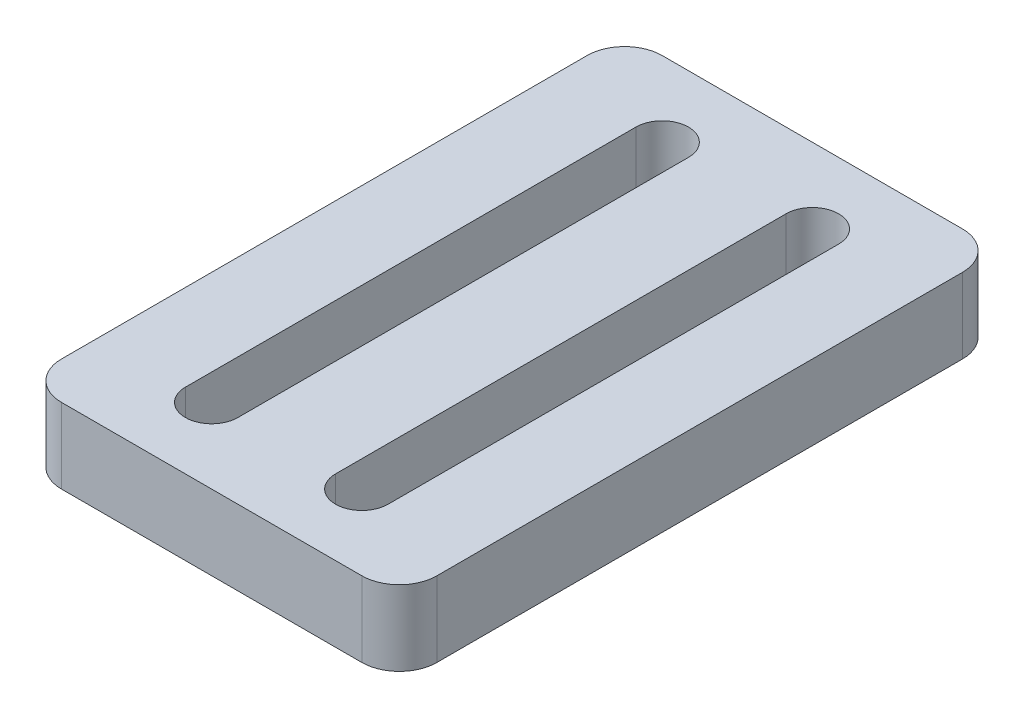
SolidWorks part; units mm, degrees
ref_plane "Front Plane" through (0, 0, 0) normal (0, 0, 1) x (1, 0, 0)
ref_plane "Top Plane" through (0, 0, 0) normal (0, 1, 0) x (1, 0, 0)
ref_plane "Right Plane" through (0, 0, 0) normal (1, 0, 0) x (0, 0, -1)
sketch "Sketch1" plane through (0, 0, 0) normal (0, 1, 0) x (1, 0, 0)
  line L1 (-12.5, -20) -> (12.5, -20)
  line L2 (-12.5, -20) -> (-12.5, 20)
  line L3 (-12.5, 20) -> (12.5, 20)
  line L4 (12.5, -20) -> (12.5, 20)
  line L5 (-12.5, -20) -> (12.5, 20) construction
  line L6 (-12.5, 20) -> (12.5, -20) construction
  point P0 (0, 0)
  dimension "D1" = 25
  dimension "D2" = 40
extrude "Boss-Extrude1" add sketch "Sketch1" along normal blind 5
sketch "Sketch2" plane through (0, 5, 0) normal (0, 1, 0) x (1, 0, 0)
  line L0 (-5, 15) -> (-5, -15) construction
  line L1 (-3.25, 15) -> (-3.25, -15)
  line L2 (-6.75, 15) -> (-6.75, -15)
  line L3 (12.5, 20) -> (-12.5, 20) construction
  line L4 (-12.5, 20) -> (-12.5, -20) construction
  line L5 (-12.5, -20) -> (12.5, -20) construction
  line L6 (0, 0) -> (0, 19.657) construction
  line L7 (5, 15) -> (5, -15) construction
  line L8 (3.25, 15) -> (3.25, -15)
  line L9 (6.75, 15) -> (6.75, -15)
  arc A0 (-3.25, 15) -> (-6.75, 15) centre (-5, 15) ccw
  arc A1 (-6.75, -15) -> (-3.25, -15) centre (-5, -15) ccw
  arc A2 (3.25, 15) -> (6.75, 15) centre (5, 15) cw
  arc A3 (6.75, -15) -> (3.25, -15) centre (5, -15) cw
  point P2 (-5, 0)
  point P18 (5, 0)
  dimension "D1" = 1.75
  dimension "D2" = 5
  dimension "D3" = 7.5
  dimension "D4" = 5
extrude "Cut-Extrude1" cut sketch "Sketch2" against normal up to surface (5 mm away) up to face at (0, 0, 0)
fillet "Fillet1" radius 2.5 4 edges at (12.5, 2.5, -20) (-12.5, 2.5, -20) (12.5, 2.5, 20) (-12.5, 2.5, 20)
